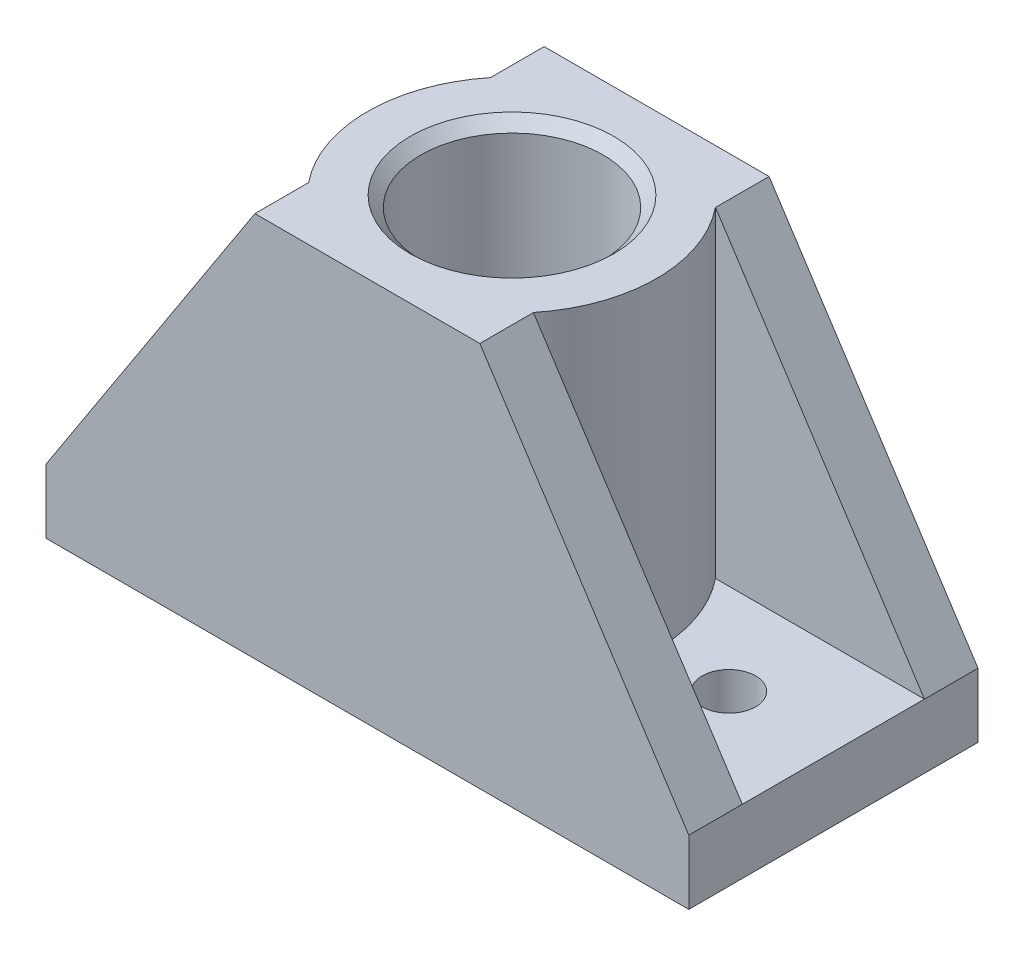
SolidWorks part; units mm, degrees
material "Nylon 6/10"
ref_plane "Front Plane" through (0, 0, 0) normal (0, 0, 1) x (1, 0, 0)
ref_plane "Top Plane" through (0, 0, 0) normal (0, 1, 0) x (1, 0, 0)
ref_plane "Right Plane" through (0, 0, 0) normal (1, 0, 0) x (0, 0, -1)
sketch "Sketch1" plane through (0, 0, 0) normal (0, 1, 0) x (1, 0, 0)
  line L1 (-106.0403, 16.2218) -> (-46.0403, 16.2218)
  line L2 (-106.0403, 16.2218) -> (-106.0403, -10.7782)
  line L3 (-106.0403, -10.7782) -> (-46.0403, -10.7782)
  line L4 (-46.0403, 16.2218) -> (-46.0403, -10.7782)
  dimension "D1" = 27
  dimension "D2" = 60
extrude "Boss-Extrude1" add sketch "Sketch1" along normal blind 6
sketch "Sketch2" plane through (0, 6, 0) normal (0, 1, 0) x (1, 0, 0)
  line L0 (-106.0403, 16.2218) -> (-46.0403, -10.7782) construction
  circle A0 centre (-76.0403, 2.7218) radius 8.5
  circle A1 centre (-76.0403, 2.7218) radius 13.5
  dimension "D1" = 17
  dimension "D2" = 27
extrude "Boss-Extrude2" add sketch "Sketch2" along normal blind 30
sketch "Sketch3" plane through (0, 6, 0) normal (0, 1, 0) x (1, 0, 0)
  line L0 (-46.0403, -10.7782) -> (-46.0403, 16.2218) construction
  line L1 (-106.0403, 16.2218) -> (-46.0403, 16.2218)
  line L2 (-106.0403, 16.2218) -> (-106.0403, 11.2218)
  line L3 (-106.0403, 11.2218) -> (-46.0403, 11.2218)
  line L4 (-46.0403, 16.2218) -> (-46.0403, 11.2218)
  line L5 (-106.0403, 16.2218) -> (-106.0403, -10.7782) construction
  line L6 (-46.0403, -10.7782) -> (-106.0403, -10.7782)
  line L7 (-46.0403, -10.7782) -> (-46.0403, -5.7782)
  line L8 (-46.0403, -5.7782) -> (-106.0403, -5.7782)
  line L9 (-106.0403, -10.7782) -> (-106.0403, -5.7782)
  dimension "D1" = 5
  dimension "D2" = 5
extrude "Boss-Extrude3" add sketch "Sketch3" along normal blind 30
chamfer "Chamfer1" distance 30 distance2 19.5 4 edges at (-46.0403, 36, 8.2782) (-46.0403, 36, -13.7218) (-106.0403, 36, 8.2782) (-106.0403, 36, -13.7218)
sketch "Sketch5" plane through (0, 6, 0) normal (0, 1, 0) x (1, 0, 0)
  line L0 (-65.5522, -5.7782) -> (-46.0403, 11.2218) construction
  line L1 (-46.0403, 11.2218) -> (-106.0403, 11.2218) construction
  line L2 (-106.0403, 11.2218) -> (-86.5284, -5.7782) construction
  circle A0 centre (-96.2844, 2.7218) radius 2.5
  circle A1 centre (-55.7963, 2.7218) radius 2.5
  dimension "D1" = 5
  dimension "D2" = 5
extrude "Cut-Extrude1" cut sketch "Sketch5" against normal blind 30
chamfer "Chamfer3" distance 1 angle 45 1 edges at (-76.0403, 36, 5.7782)
